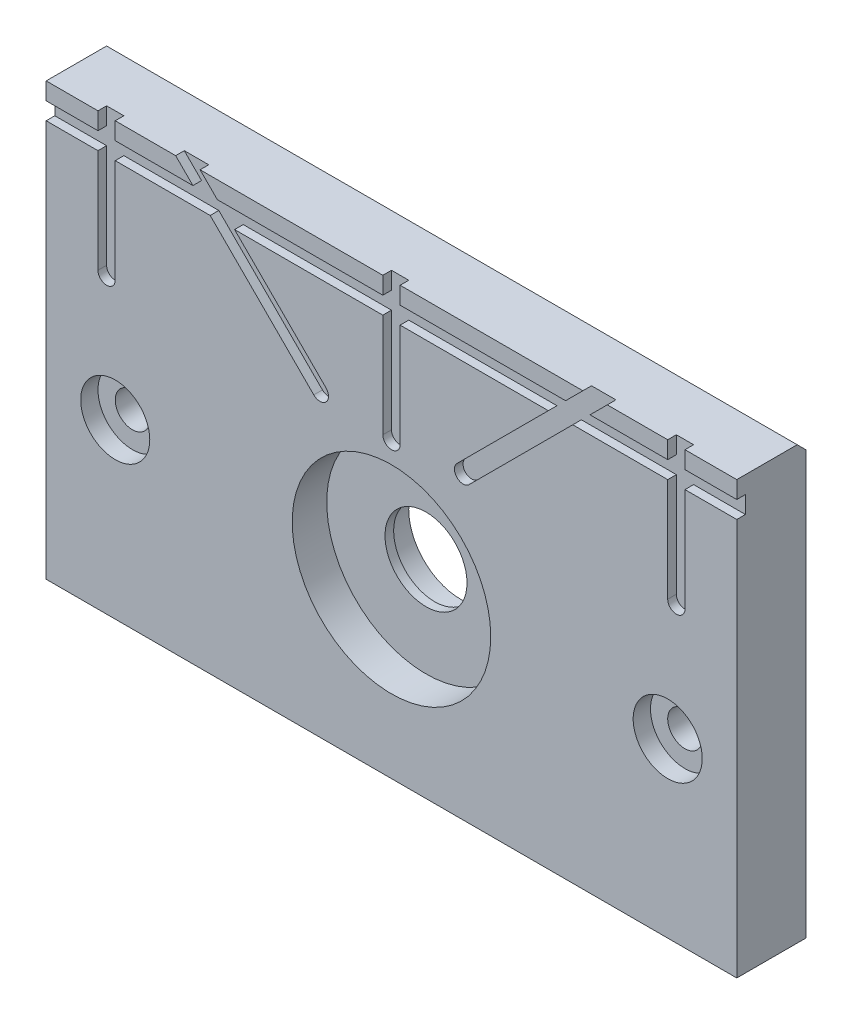
SolidWorks part; units mm, degrees
ref_plane "前视基准面" through (0, 0, 0) normal (0, 0, 1) x (1, 0, 0)
ref_plane "上视基准面" through (0, 0, 0) normal (0, 1, 0) x (1, 0, 0)
ref_plane "右视基准面" through (0, 0, 0) normal (1, 0, 0) x (0, 0, -1)
other "Configuration Table"
ref_plane "基准面1" through (0, 0, 8) normal (0, 0, 1) x (1, 0, 0)
sketch "草图1" plane through (0, 0, 8) normal (0, 0, 1) x (1, 0, 0)
  line L0 (80, -19.1667) -> (80, 40.8333)
  line L1 (80, 40.8333) -> (0, 40.8333)
  line L2 (0, 40.8333) -> (0, -19.1667)
  line L3 (0, -19.1667) -> (80, -19.1667)
  dimension "D1" = 80
  dimension "D2" = 60
extrude "凸台-拉伸1" add sketch "草图1" against normal blind 8
hole_wizard "M3.5 六角头机械螺钉的柱形沉头孔1" positions "草图13" profile "草图12" counterbore size "M3.5" standard "ANSI Metric" end condition through all
sketch "草图13" plane through (0, 0, 8) normal (0, 0, 1) x (1, 0, 0)
  line L1 (0, 10.8333) -> (80, 10.8333) construction
  line L2 (0, 40.8333) -> (0, -19.1667) construction
  line L3 (80, -19.1667) -> (80, 40.8333) construction
  point P0 (8, 10.8333)
  point P1 (72, 10.8333)
  dimension "D1" = 8
  dimension "D2" = 8
sketch "草图12" plane through (8, 10.8333, 8) normal (1, 0, 0) x (0, -1, 0)
  line L0 (0, 0) -> (0, 8)
  line L1 (0, 8) -> (2, 8)
  line L3 (2, 8) -> (2, 2)
  line L4 (2, 2) -> (4, 2)
  line L5 (4, 2) -> (4, 0)
  line L7 (4, 0) -> (0, 0)
  line L11 (0, -6.35) -> (0, 107.95) construction
  dimension "通孔孔直径" = 4
  dimension "通孔孔深度" = 8
  dimension "柱形沉头孔直径" = 8
  dimension "柱形沉头孔深度" = 2
sketch "草图14" plane through (0, 0, 8) normal (0, 0, 1) x (1, 0, 0)
  line L0 (40, 40.8333) -> (40, -19.1667) construction
  line L1 (80, 40.8333) -> (0, 40.8333) construction
  line L2 (0, -19.1667) -> (80, -19.1667) construction
  line L3 (0, 40.8333) -> (0, -19.1667) construction
  line L4 (0, 38.8333) -> (80, 38.8333)
  line L5 (0, 38.8333) -> (0, 36.8333)
  line L6 (0, 36.8333) -> (80, 36.8333)
  line L7 (40, 38.8333) -> (40, 36.8333)
  line L8 (80, -19.1667) -> (80, 40.8333) construction
  line L9 (15, 40.8333) -> (31, 24.8333)
  line L10 (6, 40.8333) -> (8, 40.8333)
  line L11 (6, 40.8333) -> (6, 24.8333)
  line L12 (6, 24.8333) -> (8, 24.8333)
  line L13 (8, 40.8333) -> (8, 24.8333)
  line L18 (39, 40.8333) -> (41, 40.8333)
  line L19 (39, 40.8333) -> (39, 24.8333)
  line L20 (39, 24.8333) -> (41, 24.8333)
  line L21 (40, 40.8333) -> (40, 24.8333)
  line L22 (31, 24.8333) -> (32.4142, 26.2475)
  line L23 (32.4142, 26.2475) -> (16.4142, 42.2475)
  line L24 (16.4142, 42.2475) -> (15, 40.8333)
  line L25 (0, 24.8333) -> (80, 24.8333) construction
  line L26 (74, 24.8333) -> (72, 24.8333)
  line L27 (72, 40.8333) -> (72, 24.8333)
  line L28 (74, 40.8333) -> (72, 40.8333)
  line L29 (74, 40.8333) -> (74, 24.8333)
  line L30 (47.5858, 26.2475) -> (63.5858, 42.2475)
  line L31 (49, 24.8333) -> (47.5858, 26.2475)
  line L32 (65, 40.8333) -> (49, 24.8333)
  line L33 (63.5858, 42.2475) -> (65, 40.8333)
  line L34 (41, 40.8333) -> (41, 24.8333)
  line L35 (80, 38.8333) -> (80, 36.8333)
  dimension "D1" = 2
  dimension "D2" = 2
  dimension "D3" = 6
  dimension "D4" = 2
  dimension "D5" = 16
  dimension "D6" = 2
  dimension "D7" = 1
  dimension "D8" = 7
  dimension "D9" = 45
extrude "切除-拉伸1" cut sketch "草图14" against normal blind 1 contours L4 L35 L6 L5 | L13 L12 L11 L10 | L9 L22 L23 L24 | L19 L20 L34 L18 | L30 L33 L32 L31 | L27 L26 L29 L28
sketch "草图15" plane through (0, 0, 8) normal (0, 0, 1) x (1, 0, 0)
  line L0 (40, 40.8333) -> (40, -19.1667) construction
  line L1 (39, 40.8333) -> (41, 40.8333) construction
  line L2 (0, -19.1667) -> (80, -19.1667) construction
  circle A0 centre (40, 10.8333) radius 4.75
  point P9 (40, 10.8333)
  dimension "D1" = 9.5
extrude "切除-拉伸2" cut sketch "草图15" against normal up to next
sketch "草图17" plane through (0, 0, 8) normal (0, 0, 1) x (1, 0, 0)
  circle A0 centre (40, 10.8333) radius 11.5
  dimension "D1" = 23
extrude "切除-拉伸4" cut sketch "草图17" against normal blind 4
sketch "草图18" plane through (0, 0, 0) normal (0, 0, -1) x (-1, 0, 0)
  circle A0 centre (-40, 10.8333) radius 6
  dimension "D1" = 12
extrude "切除-拉伸5" cut sketch "草图18" against normal blind 3
chamfer "倒角1" distance 1.5 angle 45 2 edges at (74, 10.8333, 0) (10, 10.8333, 0)
chamfer "倒角2" distance 1 angle 45 1 edges at (40, 40.8333, 0)
sketch "草图20" plane through (0, 0, 8) normal (0, 0, 1) x (1, 0, 0)
  line L0 (80, -19.1667) -> (80, 36.8333) construction
  line L1 (0, -19.1667) -> (80, -19.1667)
  line L2 (0, -19.1667) -> (0, -13.1667)
  line L3 (0, -13.1667) -> (80, -13.1667)
  line L4 (80, -19.1667) -> (80, -13.1667)
  dimension "D1" = 6
extrude "切除-拉伸6" cut sketch "草图20" against normal blind 1
sketch "草图21" plane through (0, 0, 7) normal (0, 0, 1) x (1, 0, 0)
  line L0 (80, -19.1667) -> (80, -13.1667) construction
  line L1 (0, -19.1667) -> (80, -19.1667)
  line L2 (0, -19.1667) -> (0, -15.1667)
  line L3 (0, -15.1667) -> (80, -15.1667)
  line L4 (80, -19.1667) -> (80, -15.1667)
  dimension "D1" = 4
extrude "切除-拉伸7" cut sketch "草图21" against normal blind 1
sketch "草图22" plane through (0, 0, 6) normal (0, 0, 1) x (1, 0, 0)
  line L1 (0, -19.1667) -> (80, -19.1667)
  line L2 (0, -19.1667) -> (0, -17.1667)
  line L3 (0, -17.1667) -> (80, -17.1667)
  line L4 (80, -19.1667) -> (80, -17.1667)
  dimension "D1" = 2
extrude "切除-拉伸8" cut sketch "草图22" against normal blind 1
sketch "草图23" plane through (0, 0, 8) normal (0, 0, 1) x (1, 0, 0)
  line L0 (6, 24.8333) -> (8, 24.8333) construction
  line L1 (31, 24.8333) -> (32.4142, 26.2475) construction
  line L2 (39, 24.8333) -> (41, 24.8333) construction
  line L3 (49, 24.8333) -> (47.5858, 26.2475) construction
  line L4 (74, 24.8333) -> (72, 24.8333) construction
  circle A0 centre (7, 24.8333) radius 1
  circle A1 centre (31.7071, 25.5404) radius 1
  circle A2 centre (40, 24.8333) radius 1
  circle A3 centre (48.2929, 25.5404) radius 1
  circle A4 centre (73, 24.8333) radius 1
extrude "切除-拉伸9" cut sketch "草图23" against normal up to surface (1 mm away) up to face at (40, 35.6249, 7)
sketch "草图24" plane through (0, 0, 8) normal (0, 0, 1) x (1, 0, 0)
  line L0 (0, 36.8333) -> (0, -13.1667) construction
  line L1 (0, -9.1667) -> (80, -9.1667)
  line L2 (0, -9.1667) -> (0, -19.1667)
  line L3 (0, -19.1667) -> (80, -19.1667)
  line L4 (80, -9.1667) -> (80, -19.1667)
  dimension "D1" = 10
extrude "切除-拉伸10" cut sketch "草图24" against normal up to next
